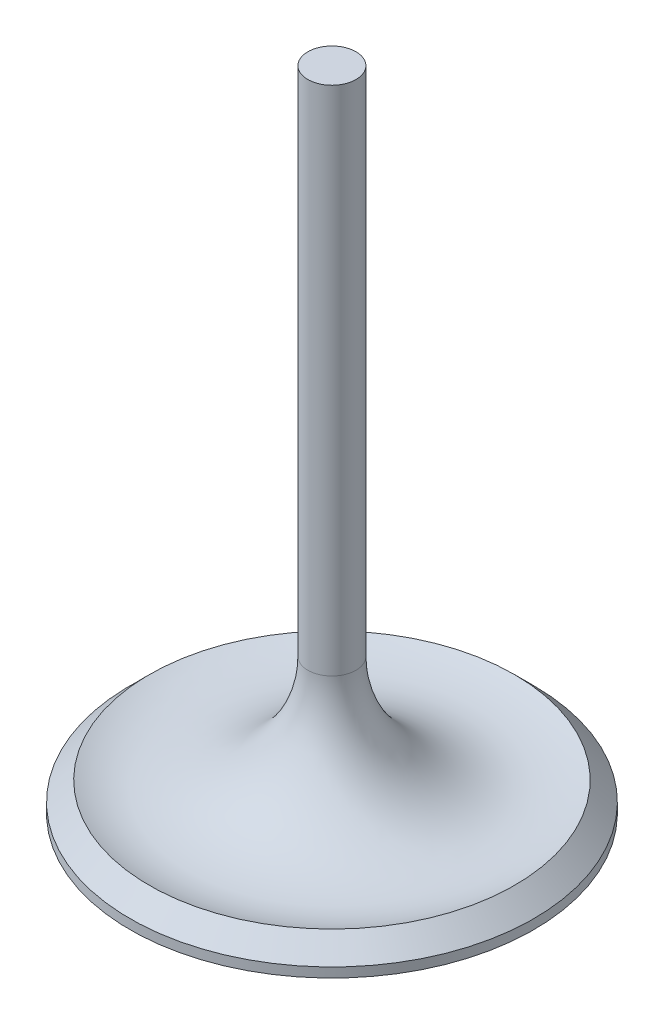
SolidWorks part; units mm, degrees
ref_plane "Front Plane" through (0, 0, 0) normal (0, 0, 1) x (1, 0, 0)
ref_plane "Top Plane" through (0, 0, 0) normal (0, 1, 0) x (1, 0, 0)
ref_plane "Right Plane" through (0, 0, 0) normal (1, 0, 0) x (0, 0, -1)
sketch "Sketch1" plane through (0, 0, 0) normal (0, 0, 1) x (1, 0, 0)
  line L0 (0, 0) -> (0, 85.55)
  line L1 (0, 85.55) -> (3.18, 85.55)
  line L2 (3.18, 85.55) -> (3.18, 17.9547)
  line L3 (0, 0) -> (26.67, 0)
  line L4 (26.67, 0) -> (26.67, 1.27)
  line L5 (26.67, 1.27) -> (24.13, 3.81)
  arc A0 (3.18, 17.9547) -> (24.13, 3.81) centre (18.43, 17.9547) ccw
  dimension "D7" = 15.25
  dimension "D1" = 85.55
  dimension "D2" = 26.67
  dimension "D3" = 1.27
  dimension "D4" = 3.81
  dimension "D5" = 45
  dimension "D6" = 3.18
revolve "Revolve1" add sketch "Sketch1" angle 360 about L0
